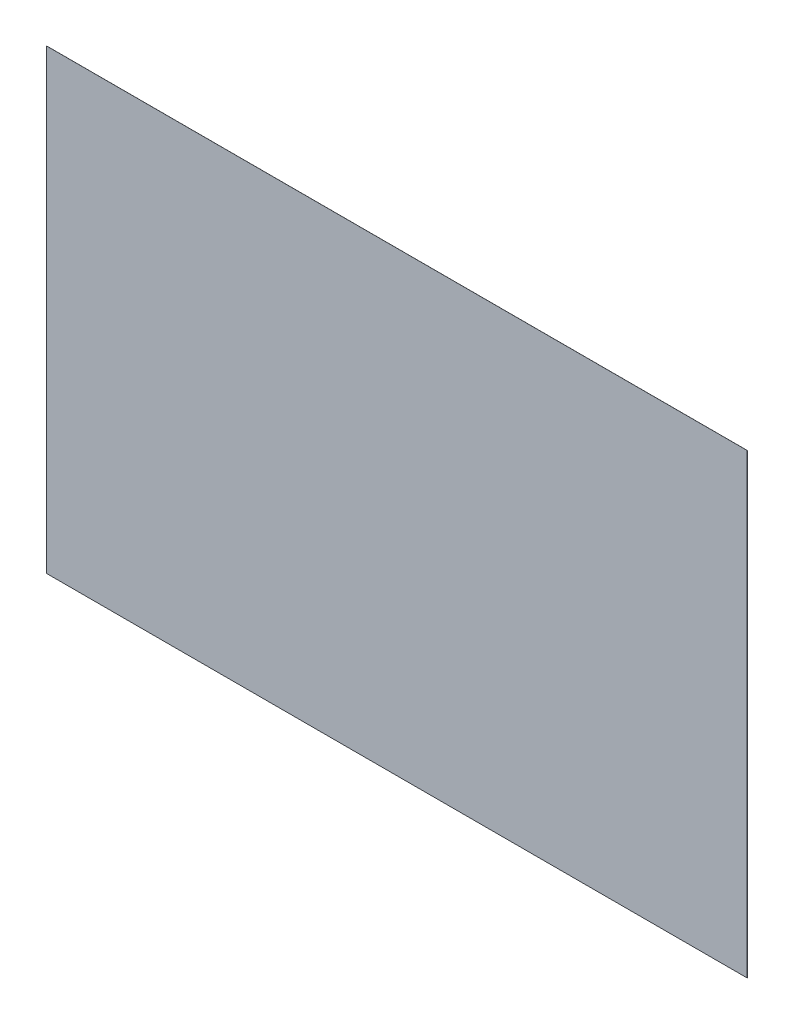
SolidWorks part; units mm, degrees
ref_plane "Front Plane" through (0, 0, 0) normal (0, 0, 1) x (1, 0, 0)
ref_plane "Top Plane" through (0, 0, 0) normal (0, 1, 0) x (1, 0, 0)
ref_plane "Right Plane" through (0, 0, 0) normal (1, 0, 0) x (0, 0, -1)
sketch "Sketch1" plane through (0, 0, 0) normal (0, 0, 1) x (1, 0, 0)
  line L12 (-287.5, 187.5) -> (287.5, -187.5) construction
  line L13 (-287.5, 187.5) -> (287.5, 187.5)
  line L14 (-287.5, 187.5) -> (-287.5, -187.5)
  line L15 (-287.5, -187.5) -> (287.5, -187.5)
  line L16 (287.5, 187.5) -> (287.5, -187.5)
  line L17 (287.5, 187.5) -> (-287.5, -187.5) construction
  point P0 (0, 0)
  dimension "D1" = 575
  dimension "D2" = 375
extrude "Boss-Extrude1" add sketch "Sketch1" along normal mid plane 0.052
